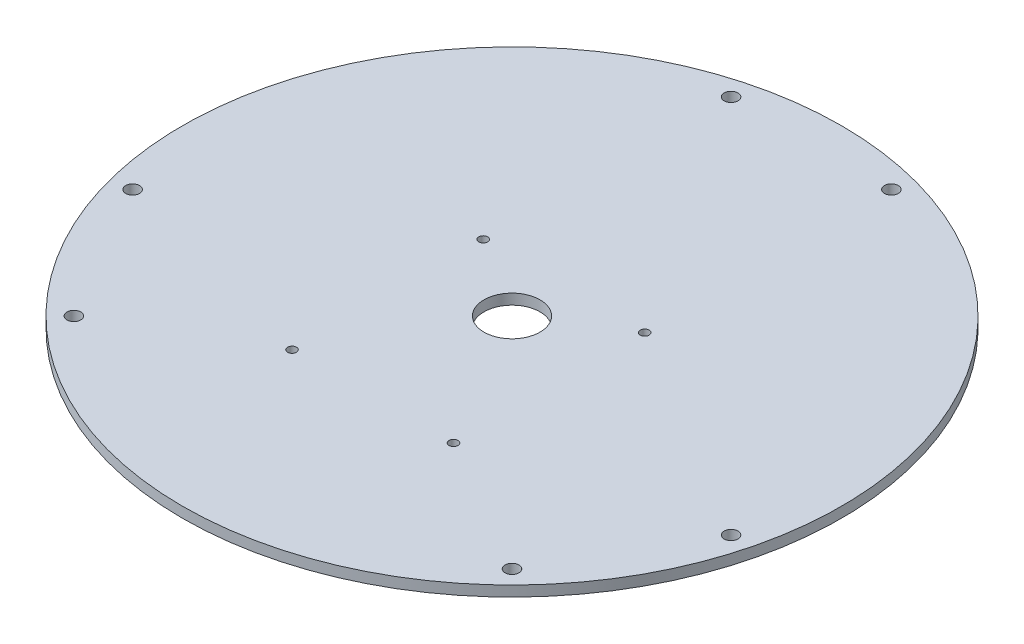
SolidWorks part; units mm, degrees
ref_plane "Front Plane" through (0, 0, 0) normal (0, 0, 1) x (1, 0, 0)
ref_plane "Top Plane" through (0, 0, 0) normal (0, 1, 0) x (1, 0, 0)
ref_plane "Right Plane" through (0, 0, 0) normal (1, 0, 0) x (0, 0, -1)
sketch "Sketch1" plane through (0, 0, 0) normal (0, 1, 0) x (1, 0, 0)
  line L0 (0, 100) -> (0, 0) construction
  line L1 (0, 0) -> (25.8819, 96.5926) construction
  line L2 (-24.5, 42.25) -> (24.5, 42.25) construction
  line L3 (-24.5, 42.25) -> (-24.5, -42.25) construction
  line L4 (-24.5, -42.25) -> (24.5, -42.25) construction
  line L5 (24.5, 42.25) -> (24.5, -42.25) construction
  line L6 (-24.5, 42.25) -> (24.5, -42.25) construction
  line L7 (-24.5, -42.25) -> (24.5, 42.25) construction
  line L8 (-24.5, -42.25) -> (24.5, -42.25) construction
  line L9 (-24.5, -42.25) -> (-24.5, 15.75) construction
  line L10 (-24.5, 15.75) -> (24.5, 15.75) construction
  line L11 (24.5, -42.25) -> (24.5, 15.75) construction
  circle A0 centre (0, 0) radius 100
  circle A1 centre (24.329, 90.797) radius 2.1
  circle A2 centre (-24.329, 90.797) radius 2.1
  circle A3 centre (90.797, -24.329) radius 2.1
  circle A4 centre (66.468, -66.468) radius 2.1
  circle A5 centre (-66.468, -66.468) radius 2.1
  circle A6 centre (-90.797, -24.329) radius 2.1
  circle A7 centre (-24.5, -42.25) radius 1.35
  circle A8 centre (24.5, -42.25) radius 1.35
  circle A9 centre (24.5, 15.75) radius 1.35
  circle A10 centre (-24.5, 15.75) radius 1.35
  circle A11 centre (0, 0) radius 8.5
  point P20 (0, 0)
  point P28 (0, 0)
  dimension "D1" = 200
  dimension "D3" = 4.2
  dimension "D6" = 17
  dimension "D2" = 15
  dimension "D4" = 6
  dimension "D5" = 0
extrude "Boss-Extrude1" add sketch "Sketch1" along normal blind 3.175
